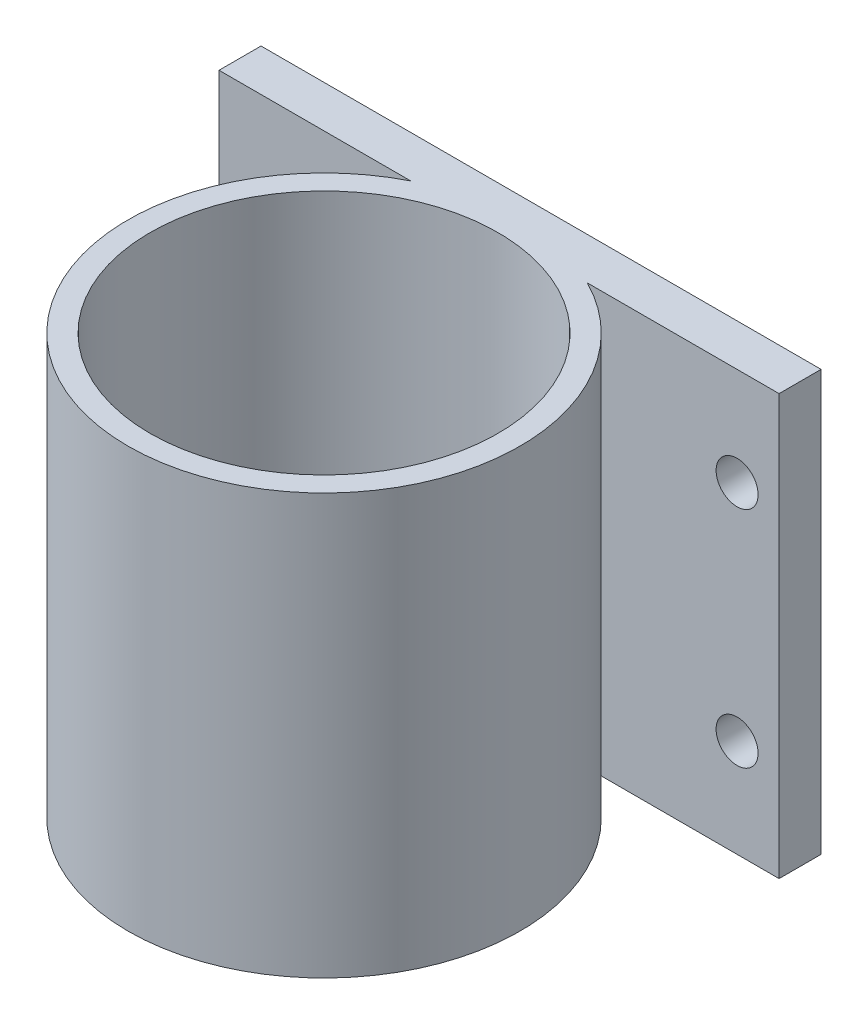
SolidWorks part; units mm, degrees
ref_plane "Front Plane" through (0, 0, 0) normal (0, 0, 1) x (1, 0, 0)
ref_plane "Top Plane" through (0, 0, 0) normal (0, 1, 0) x (1, 0, 0)
ref_plane "Right Plane" through (0, 0, 0) normal (1, 0, 0) x (0, 0, -1)
sketch "Sketch1" plane through (0, 0, 0) normal (0, 1, 0) x (1, 0, 0)
  circle A0 centre (0, 0) radius 12.425
  circle A1 centre (0, 0) radius 14
  dimension "D1" = 24.85
  dimension "D2" = 28
extrude "Boss-Extrude1" add sketch "Sketch1" along normal blind 30
sketch "Sketch2" plane through (0, 0, 0) normal (0, -1, 0) x (1, 0, 0)
  line L1 (-20, -12.5) -> (20, -12.5)
  line L2 (-20, -12.5) -> (-20, -15.5)
  line L3 (-20, -15.5) -> (20, -15.5)
  line L4 (20, -12.5) -> (20, -15.5)
  line L5 (-20, -12.5) -> (20, -15.5) construction
  line L6 (-20, -15.5) -> (20, -12.5) construction
  circle A0 centre (0, 0) radius 14 construction
  point P0 (0, -14)
  dimension "D1" = 3
  dimension "D2" = 40
extrude "Boss-Extrude2" add sketch "Sketch2" against normal blind 30
sketch "Sketch3" plane through (0, 0, -12.5) normal (0, 0, 1) x (1, 0, 0)
  line L0 (20, 30) -> (20, 0) construction
  line L1 (-20, 30) -> (-20, 0) construction
  line L2 (20, 30) -> (6.3048, 30) construction
  line L3 (-6.3048, 30) -> (-20, 30) construction
  line L4 (20, 0) -> (6.3048, 0) construction
  line L5 (-6.3048, 0) -> (-20, 0) construction
  circle A0 centre (17, 23) radius 1.5
  circle A1 centre (-17, 23) radius 1.5
  circle A2 centre (17, 7) radius 1.5
  circle A3 centre (-17, 7) radius 1.5
  dimension "D1" = 3
  dimension "D2" = 3
  dimension "D7" = 3
  dimension "D10" = 3
  dimension "D3" = 3
  dimension "D4" = 3
  dimension "D5" = 7
  dimension "D6" = 7
  dimension "D8" = 7
  dimension "D9" = 7
  dimension "D11" = 3
  dimension "D12" = 3
extrude "Cut-Extrude1" cut sketch "Sketch3" against normal blind 30
